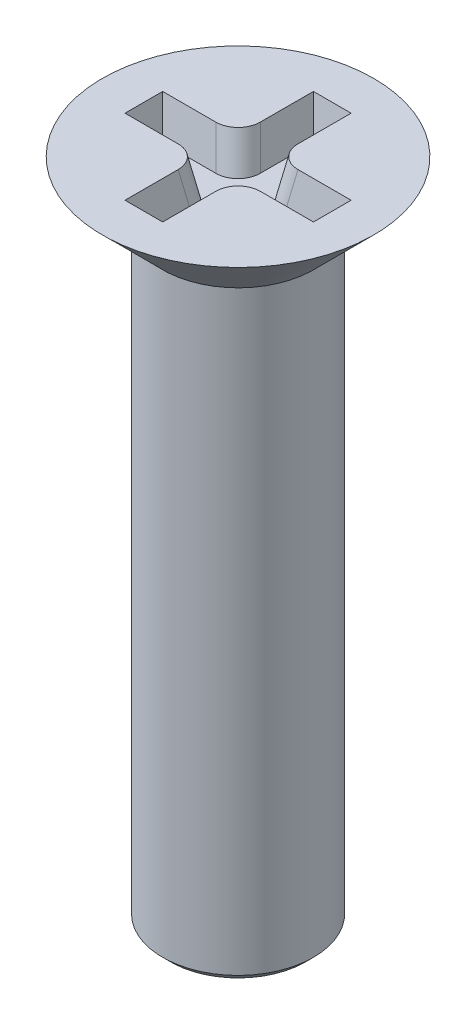
SolidWorks part; units mm, degrees
material "AISI 321 退火不锈钢 (SS)"
ref_plane "前视基准面" through (0, 0, 0) normal (0, 0, 1) x (1, 0, 0)
ref_plane "上视基准面" through (0, 0, 0) normal (0, 1, 0) x (1, 0, 0)
ref_plane "右视基准面" through (0, 0, 0) normal (1, 0, 0) x (0, 0, -1)
other "Configuration Table"
sketch "草图1" plane through (0, 0, 0) normal (0, 0, 1) x (1, 0, 0)
  line L0 (0, 0) -> (1.8, 0)
  line L1 (1.8, 0) -> (1, -0.8)
  line L2 (1, -0.8) -> (0, -0.8)
  line L3 (0, -0.8) -> (0, 0)
  dimension "D1" = 1.8
  dimension "D2" = 0.8
  dimension "D3" = 1
revolve "旋转1" add sketch "草图1" angle 360 about L3
sketch "草图2" plane through (0, -0.8, 0) normal (0, -1, 0) x (1, 0, 0)
  circle A1 centre (0, 0) radius 1
  circle A2 centre (0, 0) radius 1
  dimension "D1" = 0
extrude "凸台-拉伸1" add sketch "草图2" along normal blind 8
cosmetic thread "装饰螺纹线1" parameters "D2"=1.567
chamfer "倒角1" distance 0.1 angle 45 1 edges at (0, -8.8, -1)
sketch "草图3" plane through (0, 0, 0) normal (0, 1, 0) x (1, 0, 0)
  line L1 (-1.25, -0.25) -> (1.25, -0.25)
  line L2 (-1.25, -0.25) -> (-1.25, 0.25)
  line L3 (-1.25, 0.25) -> (1.25, 0.25)
  line L4 (1.25, -0.25) -> (1.25, 0.25)
  line L5 (-1.25, -0.25) -> (1.25, 0.25) construction
  line L6 (-1.25, 0.25) -> (1.25, -0.25) construction
  line L7 (-0.25, 1.25) -> (0.25, 1.25)
  line L8 (-0.25, 1.25) -> (-0.25, -1.25)
  line L9 (-0.25, -1.25) -> (0.25, -1.25)
  line L10 (0.25, 1.25) -> (0.25, -1.25)
  line L11 (-0.25, 1.25) -> (0.25, -1.25) construction
  line L12 (-0.25, -1.25) -> (0.25, 1.25) construction
  point P0 (0, 0)
  point P6 (0, 0)
  dimension "D1" = 0.5
  dimension "D2" = 0.5
  dimension "D3" = 2.5
  dimension "D4" = 2.5
extrude "切除-拉伸1" cut sketch "草图3" against normal blind 0.5 draft 10 contours L3 L10 L1 L4 | L10 L7 L8 L3 | L8 L3 L2 L1 | L10 L3 L8 L1 | L10 L1 L8 L9
fillet "圆角1" radius 0.3 4 edges at (-0.2059, -0.25, -0.2059) (0.2059, -0.25, -0.2059) (-0.2059, -0.25, 0.2059) (0.2059, -0.25, 0.2059)
